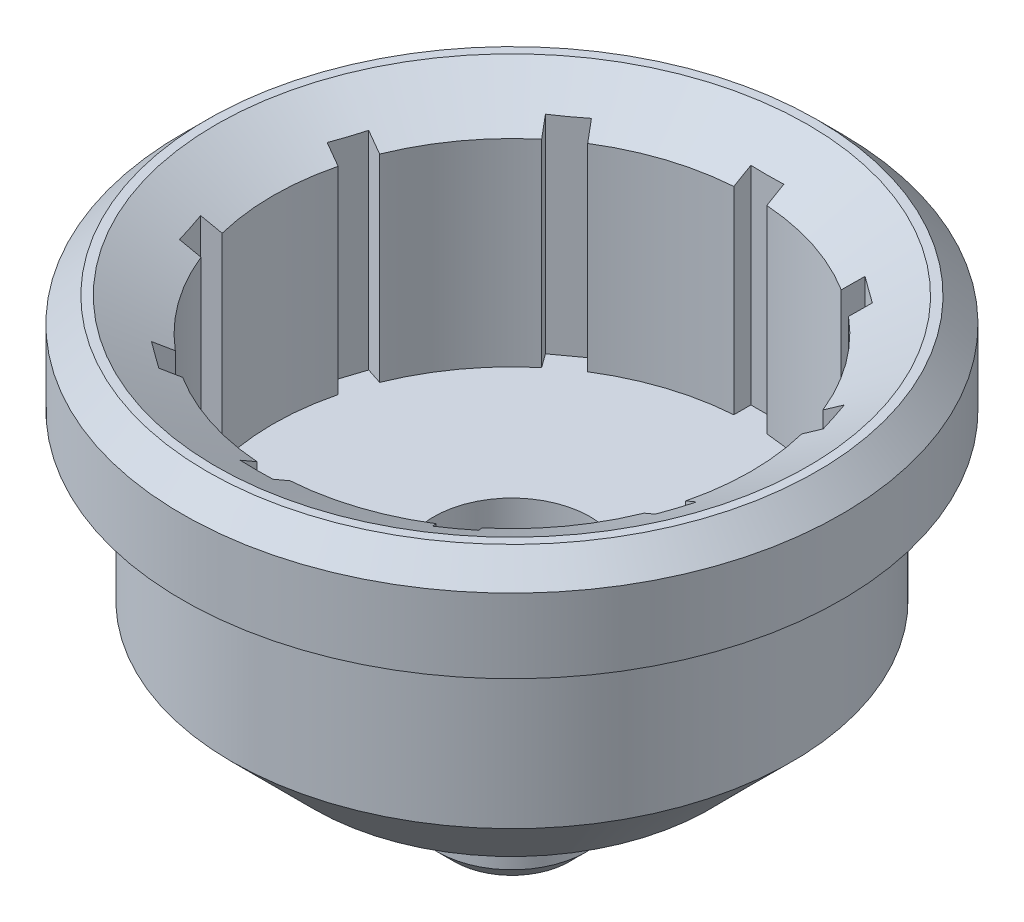
SolidWorks part; units mm, degrees
ref_plane "前视基准面" through (0, 0, 0) normal (0, 0, 1) x (1, 0, 0)
ref_plane "上视基准面" through (0, 0, 0) normal (0, 1, 0) x (1, 0, 0)
ref_plane "右视基准面" through (0, 0, 0) normal (1, 0, 0) x (0, 0, -1)
sketch "草图1" plane through (0, 0, 0) normal (0, 0, 1) x (1, 0, 0)
  line L0 (0, 0) -> (-2.5, 0) construction
  line L1 (-2.5, 0) -> (-2.5, 10)
  line L2 (-2.5, 10) -> (-4.75, 10)
  line L3 (-4.75, 10) -> (-4.75, 14)
  line L4 (-4.75, 14) -> (-14.5, 14)
  line L5 (-14.5, 14) -> (-14.5, 28)
  line L6 (-14.5, 28) -> (-20, 28)
  line L7 (-20, 28) -> (-20, 22)
  line L8 (-20, 22) -> (-17, 22)
  line L9 (-17, 22) -> (-17, 7)
  line L10 (-17, 7) -> (-6.5, 7)
  line L11 (-6.5, 7) -> (-6.5, 6)
  line L12 (-6.5, 6) -> (-4.5, 6)
  line L13 (-4.5, 6) -> (-4.5, 0)
  line L14 (-4.5, 0) -> (-2.5, 0)
  line L15 (0, 0) -> (0, 26.4741) construction
  point P13 (-3.625, 10)
  dimension "D1" = 5
  dimension "D2" = 9
  dimension "D3" = 2
  dimension "D4" = 6
  dimension "D5" = 4
  dimension "D6" = 9.5
  dimension "D7" = 4
  dimension "D8" = 29
  dimension "D9" = 40
  dimension "D10" = 34
  dimension "D11" = 6
  dimension "D12" = 14
  dimension "D13" = 1
revolve "旋转1" add sketch "草图1" angle 360 about L15
chamfer "倒角1" distance 2 angle 60 1 edges at (0, 28, -14.5)
chamfer "倒角2" distance 1.5 angle 45 1 edges at (0, 28, -20)
sketch "草图2" plane through (0, 14, 0) normal (0, 1, 0) x (1, 0, 0)
  line L1 (-1, 15.5) -> (1, 15.5)
  line L2 (-1, 15.5) -> (-1, -15.5)
  line L3 (-1, -15.5) -> (1, -15.5)
  line L4 (1, 15.5) -> (1, -15.5)
  line L5 (-1, 15.5) -> (1, -15.5) construction
  line L6 (-1, -15.5) -> (1, 15.5) construction
  point P0 (0, 0)
  dimension "D1" = 2
  dimension "D2" = 31
extrude "切除-拉伸1" cut sketch "草图2" along normal through all
pattern_circular "阵列(圆周)1" count 10 over 360 about axis through (0, 0, 0) along (0, 1, 0) of "切除-拉伸1"
chamfer "倒角3" distance 5 angle 45 1 edges at (0, 7, -17)
chamfer "倒角4" distance 1 angle 45 1 edges at (0, 0, -4.5)
